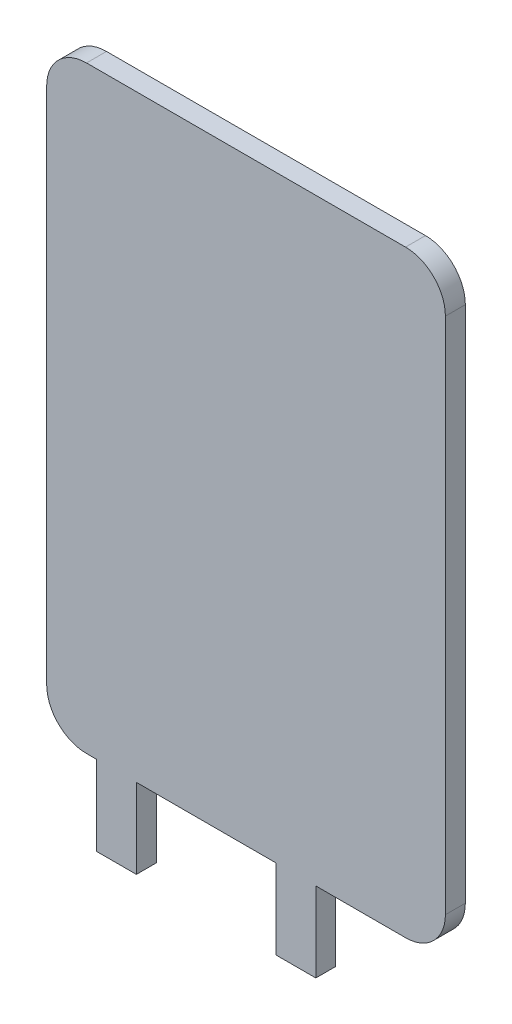
SolidWorks part; units mm, degrees
ref_plane "前视基准面" through (0, 0, 0) normal (0, 0, 1) x (1, 0, 0)
ref_plane "上视基准面" through (0, 0, 0) normal (0, 1, 0) x (1, 0, 0)
ref_plane "右视基准面" through (0, 0, 0) normal (1, 0, 0) x (0, 0, -1)
sketch "草图1" plane through (0, 0, 0) normal (0, 0, 1) x (1, 0, 0)
  line L1 (-20, 30) -> (20, 30)
  line L2 (-20, 30) -> (-20, -30)
  line L3 (-20, -30) -> (20, -30)
  line L4 (20, 30) -> (20, -30)
  line L5 (-20, 30) -> (20, -30) construction
  line L6 (-20, -30) -> (20, 30) construction
  line L7 (-15, -30) -> (-11, -30)
  line L8 (-15, -30) -> (-15, -38)
  line L9 (-15, -38) -> (-11, -38)
  line L10 (-11, -30) -> (-11, -38)
  line L11 (3, -30) -> (7, -30)
  line L12 (3, -30) -> (3, -38)
  line L13 (3, -38) -> (7, -38)
  line L14 (7, -30) -> (7, -38)
  point P0 (0, 0)
  dimension "D8" = 13
  dimension "D1" = 60
  dimension "D2" = 40
  dimension "D3" = 8
  dimension "D4" = 4
  dimension "D5" = 4
  dimension "D6" = 5
  dimension "D7" = 18
extrude "凸台-拉伸1" add sketch "草图1" along normal blind 2 contours L4 L1 L2 L3 | L10 L3 L8 L9 | L14 L3 L12 L13
fillet "圆角1" radius 4 4 edges at (20, -30, 1) (-20, -30, 1) (-20, 30, 1) (20, 30, 1)
sketch "草图2" plane through (0, 0, 2) normal (0, 0, 1) x (1, 0, 0)
  line L12 (0, 0) -> (0, -53.5) construction
  line L14 (-2.8, -38.2) -> (-7.2, -38.2)
  line L15 (-2.8, -30.2) -> (-2.8, -38.2)
  line L16 (2.8, -30.2) -> (-2.8, -30.2)
  line L18 (15.2, -38.2) -> (10.8, -38.2)
  line L19 (15.2, -30.2) -> (15.2, -38.2)
  line L20 (16, -30.2) -> (15.2, -30.2)
  line L21 (20.2, 26) -> (20.2, -26)
  line L22 (-20.2, -26) -> (-20.2, 26)
  line L23 (-15.2, -30.2) -> (-16, -30.2)
  line L24 (7.2, -30.2) -> (16, -30.2)
  line L25 (20.2, -26) -> (20.2, 26)
  line L26 (16, 30.2) -> (-16, 30.2)
  line L27 (-20.2, 26) -> (-20.2, -26)
  line L28 (-16, -30.2) -> (-15.2, -30.2)
  line L29 (-15.2, -30.2) -> (-15.2, -38.2)
  line L30 (-15.2, -38.2) -> (-10.8, -38.2)
  line L31 (-10.8, -38.2) -> (-10.8, -30.2)
  line L32 (-10.8, -30.2) -> (2.8, -30.2)
  line L33 (2.8, -30.2) -> (2.8, -38.2)
  line L34 (2.8, -38.2) -> (7.2, -38.2)
  line L35 (7.2, -38.2) -> (7.2, -30.2)
  line L36 (15.2, -30.2) -> (16, -30.2)
  line L37 (20.2, -26) -> (20.2, 26)
  line L38 (16, 30.2) -> (-16, 30.2)
  line L39 (-20.2, 26) -> (-20.2, -26)
  line L40 (-16, -30.2) -> (-15.2, -30.2)
  line L41 (-15.2, -30.2) -> (-15.2, -38.2)
  line L42 (-15.2, -38.2) -> (-10.8, -38.2)
  line L44 (-2.8, -30.2) -> (2.8, -30.2)
  line L45 (2.8, -30.2) -> (2.8, -38.2)
  line L46 (2.8, -38.2) -> (7.2, -38.2)
  arc A4 (20.2, -26) -> (16, -30.2) centre (16, -26) cw
  arc A5 (16, 30.2) -> (20.2, 26) centre (16, 26) cw
  arc A6 (-20.2, 26) -> (-16, 30.2) centre (-16, 26) cw
  arc A7 (-16, -30.2) -> (-20.2, -26) centre (-16, -26) cw
  arc A8 (16, -30.2) -> (20.2, -26) centre (16, -26) ccw
  arc A9 (20.2, 26) -> (16, 30.2) centre (16, 26) ccw
  arc A10 (-16, 30.2) -> (-20.2, 26) centre (-16, 26) ccw
  arc A11 (-20.2, -26) -> (-16, -30.2) centre (-16, -26) ccw
  arc A12 (16, -30.2) -> (20.2, -26) centre (16, -26) ccw
  arc A13 (20.2, 26) -> (16, 30.2) centre (16, 26) ccw
  arc A14 (-16, 30.2) -> (-20.2, 26) centre (-16, 26) ccw
  arc A15 (-20.2, -26) -> (-16, -30.2) centre (-16, -26) ccw
  dimension "D2" = 53.5
  dimension "D1" = 0.2
